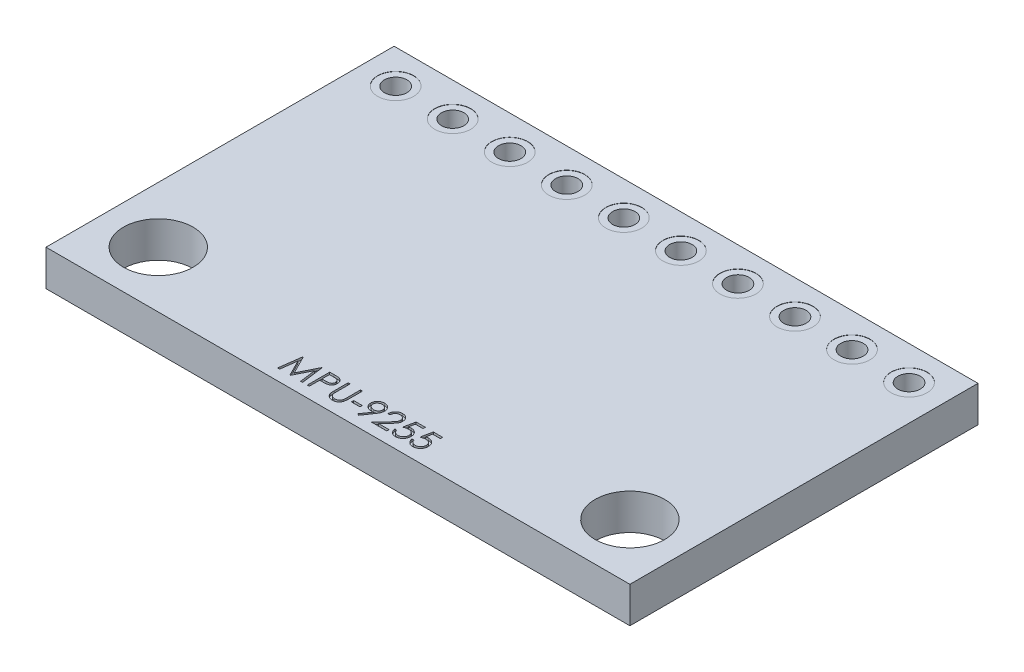
SolidWorks part; units mm, degrees
material "Polyester Resin"
ref_plane "Front Plane" through (0, 0, 0) normal (0, 0, 1) x (1, 0, 0)
ref_plane "Top Plane" through (0, 0, 0) normal (0, 1, 0) x (1, 0, 0)
ref_plane "Right Plane" through (0, 0, 0) normal (1, 0, 0) x (0, 0, -1)
sketch "BaseS" plane through (0, 0, 0) normal (0, 1, 0) x (1, 0, 0)
  line L1 (-13, 7.75) -> (13, 7.75)
  line L2 (-13, 7.75) -> (-13, -7.75)
  line L3 (-13, -7.75) -> (13, -7.75)
  line L4 (13, 7.75) -> (13, -7.75)
  line L5 (-13, 7.75) -> (13, -7.75) construction
  line L6 (-13, -7.75) -> (13, 7.75) construction
  point P0 (0, 0)
  dimension "Width" = 26
  dimension "Length" = 15.5
extrude "Base" add sketch "BaseS" along normal mid plane 1.6
sketch "HoleS" plane through (0, 0.8, 0) normal (0, 1, 0) x (1, 0, 0)
  line L0 (13, 7.75) -> (-13, 7.75) construction
  line L1 (-13, 7.75) -> (-13, -7.75) construction
  line L2 (13, 6.25) -> (11.43, 6.25) construction
  line L3 (13, -7.75) -> (13, 7.75) construction
  line L4 (-11.43, 6.25) -> (-13, 6.25) construction
  line L5 (-11.43, 6.25) -> (-8.89, 6.25) construction
  circle A0 centre (-11.43, 6.25) radius 0.5
  circle A1 centre (-8.89, 6.25) radius 0.5
  circle A2 centre (-6.35, 6.25) radius 0.5
  circle A3 centre (-3.81, 6.25) radius 0.5
  circle A4 centre (-1.27, 6.25) radius 0.5
  circle A5 centre (1.27, 6.25) radius 0.5
  circle A6 centre (3.81, 6.25) radius 0.5
  circle A7 centre (6.35, 6.25) radius 0.5
  circle A8 centre (8.89, 6.25) radius 0.5
  circle A9 centre (11.43, 6.25) radius 0.5
  dimension "Dia" = 1
  dimension "YDim" = 1.5
  dimension "Pitch" = 2.54
  dimension "NumInstances" = 10
extrude "Hole" cut sketch "HoleS" against normal through all
sketch "MountingHoleS" plane through (0, 0.8, 0) normal (0, 1, 0) x (1, 0, 0)
  line L0 (-13, 7.75) -> (-13, -7.75) construction
  line L1 (-13, -7.75) -> (13, -7.75) construction
  circle A0 centre (-10.5, -5.25) radius 1.55
  dimension "Dia" = 3.1
  dimension "XDim" = 2.5
  dimension "YDim" = 2.5
extrude "MountingHole" cut sketch "MountingHoleS" against normal through all
mirror "MH HM" about plane through (0, 0, 0) normal (1, 0, 0) of "MountingHole"
sketch "SolderingConnectionS" plane through (0, 0.8, 0) normal (0, 1, 0) x (1, 0, 0)
  circle A0 centre (-11.43, 6.25) radius 0.8
  circle A1 centre (-11.43, 6.25) radius 0.5
  circle A2 centre (-11.43, 6.25) radius 0.5 construction
  dimension "RefDia" = 1.6
  dimension "DiaControl" = 0.3
extrude "SolderingConnection" cut sketch "SolderingConnectionS" against normal blind 0.01
mirror "SC VM" about plane through (0, 0, 0) normal (0, 1, 0) of "SolderingConnection"
pattern_linear "SC LP" count 10 spacing 2.54 along (1, 0, 0) of "SolderingConnection", "SC VM"
sketch "PNSketch" plane through (0, 0.8, 0) normal (0, 1, 0) x (1, 0, 0)
  line L0 (-4, -7.25) -> (4, -7.25) construction
  line L1 (0, 0) -> (0, -7.25) construction
  line L2 (-13, -7.75) -> (13, -7.75) construction
  text T0 "MPU-9255" font "Century Gothic" height 1
  dimension "YDim" = 0.5
  dimension "Width" = 8
extrude "PN" cut sketch "PNSketch" against normal blind 0.1
